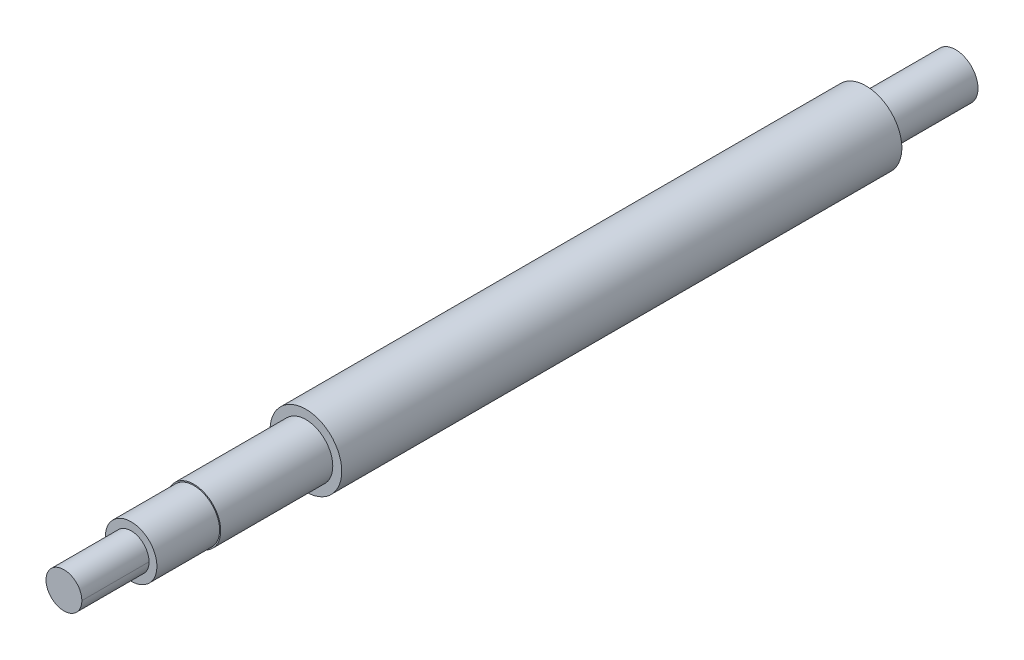
SolidWorks part; units mm, degrees
ref_plane "정면" through (0, 0, 0) normal (0, 0, 1) x (1, 0, 0)
ref_plane "윗면" through (0, 0, 0) normal (0, 1, 0) x (1, 0, 0)
ref_plane "우측면" through (0, 0, 0) normal (1, 0, 0) x (0, 0, -1)
sketch "스케치1" plane through (0, 0, 0) normal (0, 0, 1) x (1, 0, 0)
  circle A0 centre (0, 0) radius 5
  dimension "D1" = 10
extrude "보스-돌출1" add sketch "스케치1" along normal blind 10
sketch "스케치2" plane through (0, 0, 10) normal (0, 0, 1) x (1, 0, 0)
  circle A0 centre (0, 0) radius 8
  dimension "D1" = 16
extrude "보스-돌출2" add sketch "스케치2" along normal blind 135
sketch "스케치3" plane through (0, 0, 145) normal (0, 0, 1) x (1, 0, 0)
  circle A0 centre (0, 0) radius 6
  dimension "D1" = 12
extrude "보스-돌출3" add sketch "스케치3" along normal blind 25
sketch "스케치4" plane through (0, 0, 170) normal (0, 0, 1) x (1, 0, 0)
  circle A0 centre (0, 0) radius 5.75
  dimension "D1" = 11.5
extrude "보스-돌출4" add sketch "스케치4" along normal blind 14
sketch "스케치5" plane through (0, 0, 184) normal (0, 0, 1) x (1, 0, 0)
  circle A0 centre (0, 0) radius 4
  dimension "D1" = 8
extrude "보스-돌출5" add sketch "스케치5" along normal blind 15
split line "분할선1"
sketch "스케치6" plane through (0, 0, 10) normal (0, 0, -1) x (-1, 0, 0)
  circle A0 centre (0, 0) radius 5
  circle A1 centre (0, 0) radius 8
extrude "컷-돌출1" cut sketch "스케치6" against normal blind 10
